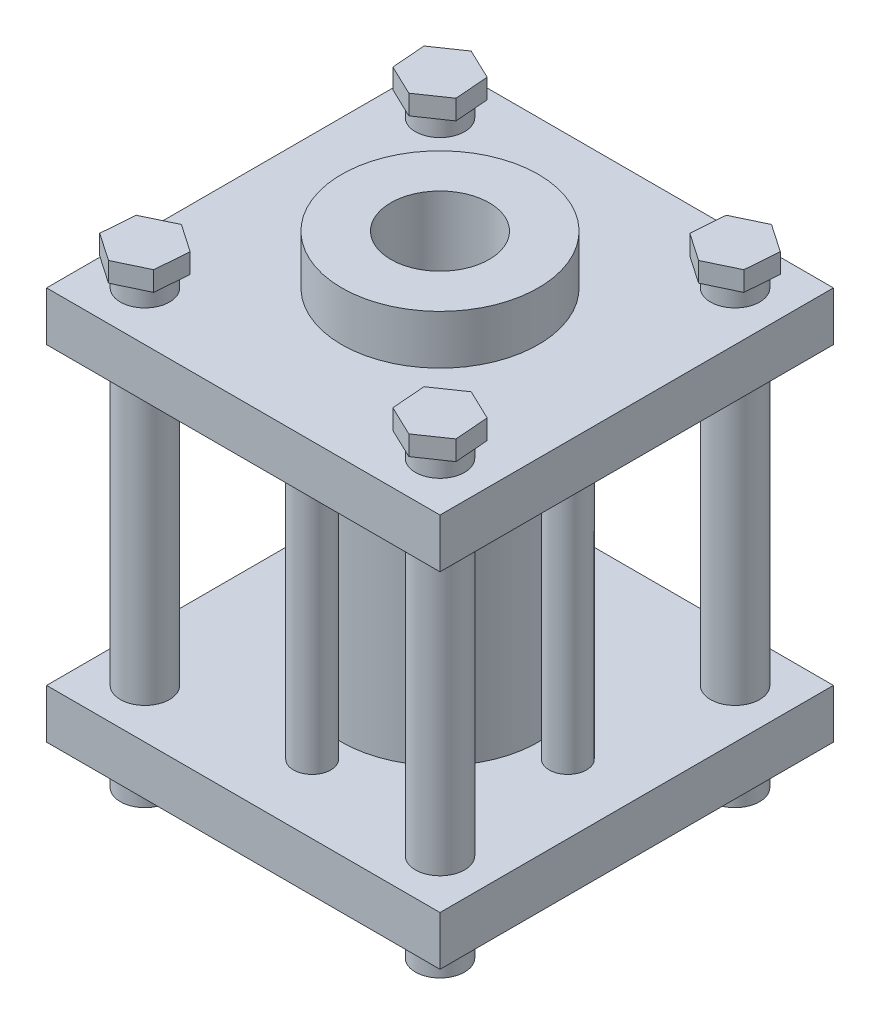
SolidWorks part; units mm, degrees
ref_plane "Front Plane" through (0, 0, 0) normal (0, 0, 1) x (1, 0, 0)
ref_plane "Top Plane" through (0, 0, 0) normal (0, 1, 0) x (1, 0, 0)
ref_plane "Right Plane" through (0, 0, 0) normal (1, 0, 0) x (0, 0, -1)
sketch "Sketch1" plane through (0, 0, 0) normal (0, 1, 0) x (1, 0, 0)
  line L0 (-66.6676, 0) -> (71.4042, 0) construction
  line L1 (-50.8, 50.8) -> (50.8, 50.8)
  line L2 (-50.8, 50.8) -> (-50.8, -50.8)
  line L3 (-50.8, -50.8) -> (50.8, -50.8)
  line L4 (50.8, 50.8) -> (50.8, -50.8)
  line L5 (-50.8, 50.8) -> (50.8, -50.8) construction
  line L6 (-50.8, -50.8) -> (50.8, 50.8) construction
  line L7 (0, 78.9828) -> (0, -79.2196) construction
  circle A0 centre (-38.1, 38.1) radius 6.35
  circle A1 centre (38.1, 38.1) radius 6.35
  circle A2 centre (38.1, -38.1) radius 6.35
  circle A3 centre (-38.1, -38.1) radius 6.35
  point P0 (0, 0)
  dimension "D3" = 12.7
  dimension "D1" = 101.6
  dimension "D2" = 101.6
extrude "Boss-Extrude1" add sketch "Sketch1" along normal blind 12.7
sketch "Sketch2" plane through (0, 12.7, 0) normal (0, 1, 0) x (1, 0, 0)
  line L0 (0, 54.6234) -> (0, -59.772) construction
  line L1 (-54.3016, 0) -> (53.6581, 0) construction
  circle A0 centre (0, 0) radius 25.4
  circle A1 centre (0, 0) radius 33.02 construction
  circle A2 centre (0, 33.02) radius 4.826
  circle A3 centre (0.001, 0.001) radius 33.02 construction
  circle A4 centre (33.021, 0.001) radius 4.826
  circle A5 centre (0.002, 0) radius 33.02 construction
  circle A6 centre (0.002, -33.02) radius 4.826
  circle A7 centre (0.001, -0.001) radius 33.02 construction
  circle A8 centre (-33.019, -0.001) radius 4.826
  point P25 (0.001, 0)
  dimension "D1" = 4
extrude "Boss-Extrude2" add sketch "Sketch2" along normal blind 76.2 separate body
ref_plane "Plane1" through (0, 91.44, 0) normal (0, 1, 0) x (1, 0, 0)
sketch "Sketch4" plane through (0, 88.9, 0) normal (0, 1, 0) x (1, 0, 0)
  line L4 (50.8, -50.8) -> (50.8, 50.8)
  line L5 (50.8, 50.8) -> (-50.8, 50.8)
  line L6 (-50.8, 50.8) -> (-50.8, -50.8)
  line L7 (-50.8, -50.8) -> (50.8, -50.8)
  line L8 (50.8, -50.8) -> (50.8, 50.8)
  line L9 (50.8, 50.8) -> (-50.8, 50.8)
  line L10 (-50.8, 50.8) -> (-50.8, -50.8)
  line L11 (-50.8, -50.8) -> (50.8, -50.8)
  circle A1 centre (0, 0) radius 25.4
  circle A2 centre (0, 0) radius 25.4
  dimension "D1" = 0
  dimension "D2" = 0
extrude "Boss-Extrude4" add sketch "Sketch4" along normal blind 12.7 separate body
sketch "Sketch5" plane through (0, 88.9, 0) normal (0, 1, 0) x (1, 0, 0)
  circle A0 centre (-38.1, 38.1) radius 6.35 construction
  circle A1 centre (0, 0) radius 25.4
  circle A2 centre (0, 0) radius 25.4
  circle A3 centre (38.1, -38.1) radius 6.35 construction
  circle A4 centre (-38.1, -38.1) radius 6.35 construction
  circle A5 centre (-38.1, 38.1) radius 6.35
  circle A6 centre (38.1, -38.1) radius 6.35
  circle A7 centre (-38.1, -38.1) radius 6.35
  circle A8 centre (38.1, 38.1) radius 6.35 construction
  circle A9 centre (38.1, 38.1) radius 6.35
  dimension "D1" = 0
extrude "Cut-Extrude2" cut sketch "Sketch5" along normal through all both contours A7 | A5 | A9 | A6
sketch "Sketch6" plane through (0, 88.9, 0) normal (0, 1, 0) x (1, 0, 0)
  circle A1 centre (0, 0) radius 25.4
  circle A2 centre (0, 0) radius 25.4
  dimension "D1" = 0
extrude "Boss-Extrude5" add sketch "Sketch6" along normal blind 25.4
sketch "Sketch7" plane through (0, 114.3, 0) normal (0, 1, 0) x (1, 0, 0)
  circle A0 centre (0, 0) radius 12.7
extrude "Cut-Extrude3" cut sketch "Sketch7" against normal through all both
sketch "Sketch9" plane through (0, 91.44, 0) normal (0, 1, 0) x (1, 0, 0)
  circle A0 centre (-38.1, -38.1) radius 6.35 construction
  circle A1 centre (38.1, -38.1) radius 6.35 construction
  circle A2 centre (38.1, 38.1) radius 6.35 construction
  circle A3 centre (-38.1, 38.1) radius 6.35 construction
  circle A4 centre (-38.1, -38.1) radius 6.35
  circle A5 centre (38.1, -38.1) radius 6.35
  circle A6 centre (38.1, 38.1) radius 6.35
  circle A7 centre (-38.1, 38.1) radius 6.35
extrude "Boss-Extrude6" add sketch "Sketch9" against normal blind 101.6 and the other way blind 15.24 separate body
sketch "Sketch10" plane through (0, 106.68, 0) normal (0, 1, 0) x (1, 0, 0)
  line L0 (-116.9949, 0) -> (101.6513, 0) construction
  line L1 (-30.879, -43.058) -> (-30.1958, -34.3254)
  line L2 (-30.1958, -34.3254) -> (-37.4168, -29.3674)
  line L3 (-37.4168, -29.3674) -> (-45.321, -33.142)
  line L4 (-45.321, -33.142) -> (-46.0042, -41.8746)
  line L5 (-46.0042, -41.8746) -> (-38.7832, -46.8326)
  line L6 (-38.7832, -46.8326) -> (-30.879, -43.058)
  line L7 (-38.7832, 46.8326) -> (-30.879, 43.058)
  line L8 (0, 69.5257) -> (0, -64.1554) construction
  line L9 (-46.0042, 41.8746) -> (-38.7832, 46.8326)
  line L10 (-45.321, 33.142) -> (-46.0042, 41.8746)
  line L11 (-37.4168, 29.3674) -> (-45.321, 33.142)
  line L12 (-30.1958, 34.3254) -> (-37.4168, 29.3674)
  line L13 (-30.879, 43.058) -> (-30.1958, 34.3254)
  line L14 (46.0042, 41.8746) -> (38.7832, 46.8326)
  line L15 (45.321, 33.142) -> (46.0042, 41.8746)
  line L16 (37.4168, 29.3674) -> (45.321, 33.142)
  line L17 (30.1958, 34.3254) -> (37.4168, 29.3674)
  line L18 (30.879, 43.058) -> (30.1958, 34.3254)
  line L19 (38.7832, 46.8326) -> (30.879, 43.058)
  line L20 (38.7832, -46.8326) -> (30.879, -43.058)
  line L21 (46.0042, -41.8746) -> (38.7832, -46.8326)
  line L22 (45.321, -33.142) -> (46.0042, -41.8746)
  line L23 (37.4168, -29.3674) -> (45.321, -33.142)
  line L24 (30.1958, -34.3254) -> (37.4168, -29.3674)
  line L25 (30.879, -43.058) -> (30.1958, -34.3254)
  circle A0 centre (-38.1, -38.1) radius 7.5857 construction
  point P12 (0, 0)
extrude "Boss-Extrude7" add sketch "Sketch10" along normal blind 5.08
